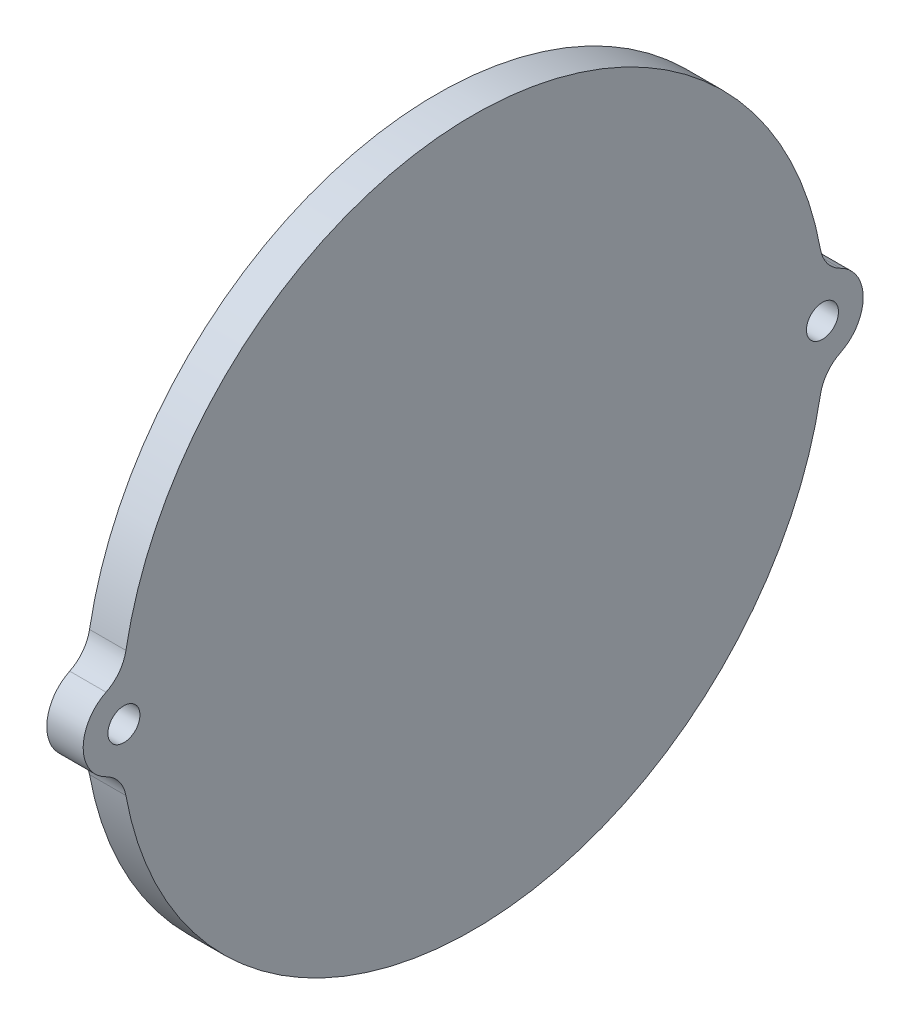
SolidWorks part; units mm, degrees
ref_plane "Front" through (0, 0, 0) normal (0, 0, 1) x (1, 0, 0)
ref_plane "Top" through (0, 0, 0) normal (0, 1, 0) x (1, 0, 0)
ref_plane "Right" through (0, 0, 0) normal (1, 0, 0) x (0, 0, -1)
sketch "Sketch1" plane through (0, 0, 0) normal (0, 0, 1) x (1, 0, 0)
  line L0 (0, 0) -> (-19.0982, 0) construction
  line L1 (0, 0) -> (0, 24.25)
  line L2 (0, 24.25) -> (-2.5, 24.25)
  line L3 (-2.5, 19) -> (-2.5, 24.25)
  line L5 (-2.5, 19) -> (-2.5, 0)
  line L6 (-8.1008, -0.6382) -> (-8.0455, -0.672)
  line L7 (-2.5, 0) -> (0, 0)
  dimension "D2" = 48.5
  dimension "D4" = 2.5
revolve "Revolve1" add sketch "Sketch1" angle 360 about L0
sketch "Sketch2" plane through (0, 0, 0) normal (1, 0, 0) x (0, 0, -1)
  line L0 (0, 0) -> (0, 14.132) construction
  circle A0 centre (-24, 0) radius 1.1
  circle A1 centre (24, 0) radius 1.1
  circle A2 centre (-24, 0) radius 2.8
  circle A3 centre (24, 0) radius 2.8
  dimension "D1" = 24
  dimension "D2" = 2.2
  dimension "D3" = 1.7
extrude "Boss-Extrude1" add sketch "Sketch2" against normal up to surface (2.5 mm away) up to face at (-2.5, 0, -24.25)
fillet "Fillet1" radius 2.5 4 edges at (-1.25, 2.7986, -24.088) (-1.25, -2.7986, -24.088) (-1.25, -2.7986, 24.088) (-1.25, 2.7986, 24.088)
sketch "Sketch4" plane through (-2.5, 0, 0) normal (-1, 0, 0) x (0, 0, 1)
  circle A1 centre (0, 0) radius 13.5 construction
  circle A2 centre (0, 0) radius 9.75
  circle A3 centre (0, 0) radius 17.25
  dimension "D1" = 27
  dimension "D4" = 7.5
  dimension "D5" = 3.75
extrude "Boss-Extrude2" add sketch "Sketch4" along normal blind 0.5
sketch "Sketch6" plane through (0, 0, 0) normal (1, 0, 0) x (0, 0, -1)
  circle A0 centre (-24, 0) radius 1.1
  circle A1 centre (24, 0) radius 1.1
  arc A2 (-24.2261, 1.0765) -> (-24.2261, -1.0765) centre (-24, 0) ccw construction
  arc A3 (24.2261, -1.0765) -> (24.2261, 1.0765) centre (24, 0) ccw construction
extrude "Cut-Extrude1" cut sketch "Sketch6" against normal through all both and the other way through all
